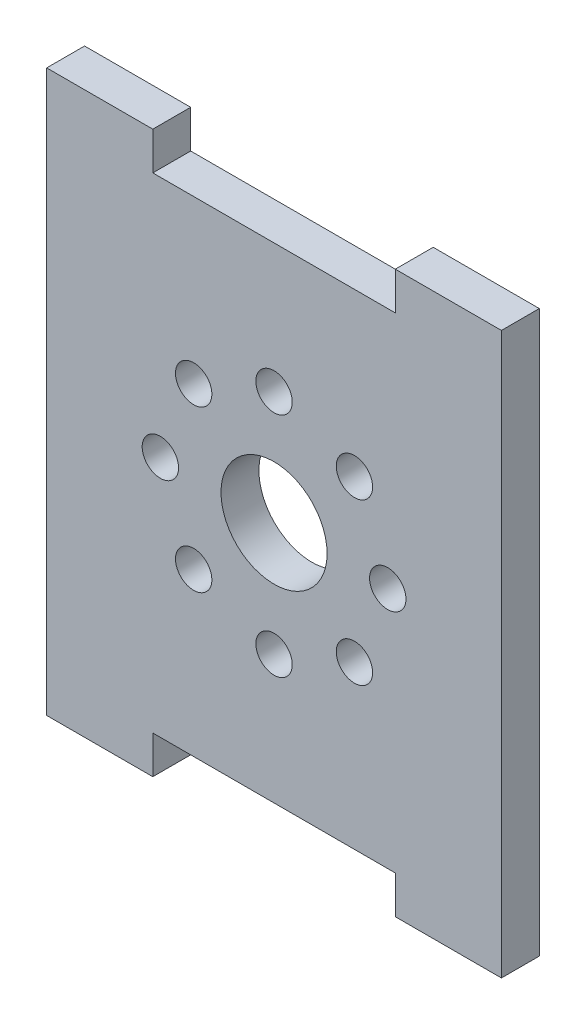
SolidWorks part; units mm, degrees
ref_plane "Plan de face" through (0, 0, 0) normal (0, 0, 1) x (1, 0, 0)
ref_plane "Plan de dessus" through (0, 0, 0) normal (0, 1, 0) x (1, 0, 0)
ref_plane "Plan de droite" through (0, 0, 0) normal (1, 0, 0) x (0, 0, -1)
sketch "Esquisse1" plane through (0, 0, 0) normal (0, 0, 1) x (1, 0, 0)
  line L1 (15, -18.5) -> (-15, -18.5)
  line L2 (15, -18.5) -> (15, 18.5)
  line L3 (15, 18.5) -> (-15, 18.5)
  line L4 (-15, -18.5) -> (-15, 18.5)
  line L5 (15, -18.5) -> (-15, 18.5) construction
  line L6 (15, 18.5) -> (-15, -18.5) construction
  line L7 (8, 16) -> (-8, 16)
  line L8 (8, 16) -> (8, 18.5)
  line L9 (8, 18.5) -> (-8, 18.5)
  line L10 (-8, 16) -> (-8, 18.5)
  line L11 (8, 16) -> (-8, 18.5) construction
  line L12 (8, 18.5) -> (-8, 16) construction
  line L13 (-8, -16) -> (8, -16)
  line L14 (-8, -16) -> (-8, -18.5)
  line L15 (-8, -18.5) -> (8, -18.5)
  line L16 (8, -16) -> (8, -18.5)
  line L17 (-8, -16) -> (8, -18.5) construction
  line L18 (-8, -18.5) -> (8, -16) construction
  circle A0 centre (0, 0) radius 3.5
  point P0 (0, 0)
  point P6 (0, 17.25)
  point P11 (0, -17.25)
  dimension "D7" = 7
  dimension "D1" = 30
  dimension "D2" = 32
  dimension "D3" = 2.5
  dimension "D4" = 2.5
  dimension "D5" = 7
  dimension "D6" = 7
extrude "Boss.-Extru.1" add sketch "Esquisse1" along normal blind 2.5 contours L13 L16 L1 L2 L3 L8 L7 L10 L4 L14 A0
hole_wizard "Dégagement M21" positions "Esquisse5" profile "Esquisse3" hole size "M2" standard "Iso"
sketch "Esquisse5" plane through (0, 0, 2.5) normal (0, 0, 1) x (1, 0, 0)
  point P0 (0, 7.5)
  point P8 (0, 7.5)
  dimension "D1" = 7.5
sketch "Esquisse3" plane through (0, 7.5, 2.5) normal (1, 0, 0) x (0, -1, 0)
  line L0 (0, 0) -> (0, 3.221)
  line L1 (0, 3.221) -> (1.2, 2.5)
  line L2 (1.2, 2.5) -> (1.2, 0)
  line L5 (1.2, 0) -> (0, 0)
  line L10 (0, 3.221) -> (-1.2, 2.5) construction
  line L11 (0, -6.35) -> (0, 107.95) construction
  dimension "Diamètre du perçage" = 2.4
  dimension "Profondeur du perçage" = 2.5
  dimension "Angle de pointe" = 118
pattern_circular "Répétition circulaire1" count 8 over 360 about axis through (0, 0, 0) along (0, 0, 1) of "Dégagement M21"
